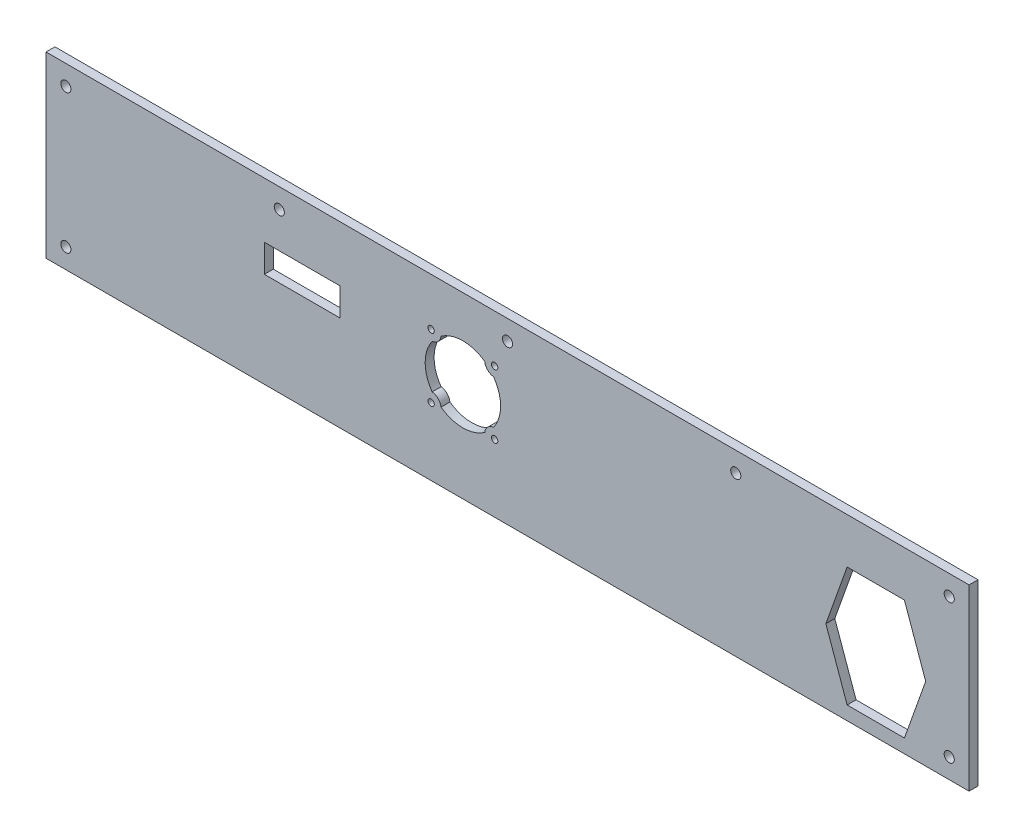
SolidWorks part; units mm, degrees
material "Acrylic (Medium-high impact)"
ref_plane "Front Plane" through (0, 0, 0) normal (0, 0, 1) x (1, 0, 0)
ref_plane "Top Plane" through (0, 0, 0) normal (0, 1, 0) x (1, 0, 0)
ref_plane "Right Plane" through (0, 0, 0) normal (1, 0, 0) x (0, 0, -1)
sketch "Sketch1" plane through (0, 0, 0) normal (0, 0, 1) x (1, 0, 0)
  line L0 (-222.5, 45) -> (-222.5, -45) construction
  line L1 (-232.5, -45) -> (232.5, -45)
  line L2 (-232.5, -45) -> (-232.5, 45)
  line L3 (-232.5, 45) -> (232.5, 45)
  line L4 (232.5, -45) -> (232.5, 45)
  line L5 (-232.5, -45) -> (232.5, 45) construction
  line L6 (-232.5, 45) -> (232.5, -45) construction
  line L7 (0, 45) -> (0, -45) construction
  line L8 (-232.5, 35) -> (2.55, 35) construction
  circle A0 centre (-222.5, 35) radius 2.55
  circle A1 centre (-222.5, -35) radius 2.55
  circle A2 centre (0, 35) radius 2.55
  circle A3 centre (-114.975, 35) radius 2.55
  circle A4 centre (222.5, -35) radius 2.55
  circle A5 centre (222.5, 35) radius 2.55
  circle A6 centre (114.975, 35) radius 2.55
  point P0 (0, 0)
  point P17 (-114.975, 35)
  dimension "D4" = 5.1
  dimension "D5" = 10
  dimension "D6" = 10
  dimension "D7" = 10
  dimension "D1" = 465
  dimension "D2" = 90
  dimension "D3" = 10
extrude "Boss-Extrude1" add sketch "Sketch1" along normal mid plane 4.4958
sketch "Sketch2" plane through (0, 0, 2.2479) normal (0, 0, 1) x (1, 0, 0)
  line L1 (-232.5, -45) -> (232.5, -45) construction
  line L2 (-122.5, 17) -> (-84.5, 17)
  line L3 (-122.5, 17) -> (-122.5, 3)
  line L4 (-122.5, 3) -> (-84.5, 3)
  line L10 (-84.5, 17) -> (-84.5, 3)
  line L11 (-232.5, 45) -> (-232.5, -45) construction
  line L23 (-38.5, -11) -> (-6.5, -11) construction
  line L24 (-38.5, -11) -> (-38.5, 21) construction
  line L25 (-38.5, 21) -> (-6.5, 21) construction
  line L26 (-6.5, -11) -> (-6.5, 21) construction
  line L27 (-38.5, -11) -> (-6.5, 21) construction
  line L28 (-38.5, 21) -> (-6.5, -11) construction
  line L29 (-42.5, -15) -> (-2.5, -15) construction
  line L30 (-42.5, -15) -> (-42.5, 25) construction
  line L31 (-42.5, 25) -> (-2.5, 25) construction
  line L32 (-2.5, -15) -> (-2.5, 25) construction
  line L33 (-42.5, -15) -> (-2.5, 25) construction
  line L34 (-42.5, 25) -> (-2.5, -15) construction
  line L45 (210.6369, -8) -> (199.9233, 22.1)
  line L46 (199.9233, -38.1) -> (210.6369, -8)
  line L47 (171.0767, -38.1) -> (199.9233, -38.1)
  line L48 (160.3631, -8) -> (171.0767, -38.1)
  line L49 (171.0767, 22.1) -> (160.3631, -8)
  line L50 (199.9233, 22.1) -> (171.0767, 22.1)
  line L51 (210.6369, -8) -> (199.9233, 22.1)
  line L52 (199.9233, -38.1) -> (210.6369, -8)
  line L53 (171.0767, -38.1) -> (199.9233, -38.1)
  line L54 (160.3631, -8) -> (171.0767, -38.1)
  line L55 (171.0767, 22.1) -> (160.3631, -8)
  line L56 (199.9233, 22.1) -> (171.0767, 22.1)
  arc A0 (-33.528, -10.472) -> (-11.472, -10.472) centre (-22.5, 5) ccw
  circle A1 centre (-6.5, 21) radius 1.6
  circle A2 centre (-38.5, 21) radius 1.6
  circle A3 centre (-38.5, -11) radius 1.6
  circle A4 centre (-6.5, -11) radius 1.6
  arc A5 (-37.972, 16.028) -> (-37.972, -6.028) centre (-22.5, 5) ccw
  arc A6 (-11.472, 20.472) -> (-7.028, 16.028) centre (-6.5, 21) ccw
  arc A7 (-11.472, 20.472) -> (-33.528, 20.472) centre (-22.5, 5) ccw
  arc A8 (-7.028, -6.028) -> (-7.028, 16.028) centre (-22.5, 5) ccw
  arc A10 (-37.972, 16.028) -> (-33.528, 20.472) centre (-38.5, 21) ccw
  arc A11 (-33.528, -10.472) -> (-37.972, -6.028) centre (-38.5, -11) ccw
  arc A12 (-7.028, -6.028) -> (-11.472, -10.472) centre (-6.5, -11) ccw
  dimension "D14" = 3.2
  dimension "D15" = 38
  dimension "D16" = 5
  dimension "D2" = 14
  dimension "D3" = 48
  dimension "D4" = 110
  dimension "D5" = 38
  dimension "D6" = 210
  dimension "D7" = 50
  dimension "D8" = 0.6
  dimension "D10" = 32
  dimension "D11" = 32
  dimension "D12" = 40
  dimension "D13" = 40
extrude "Cut-Extrude1" cut sketch "Sketch2" against normal up to next
